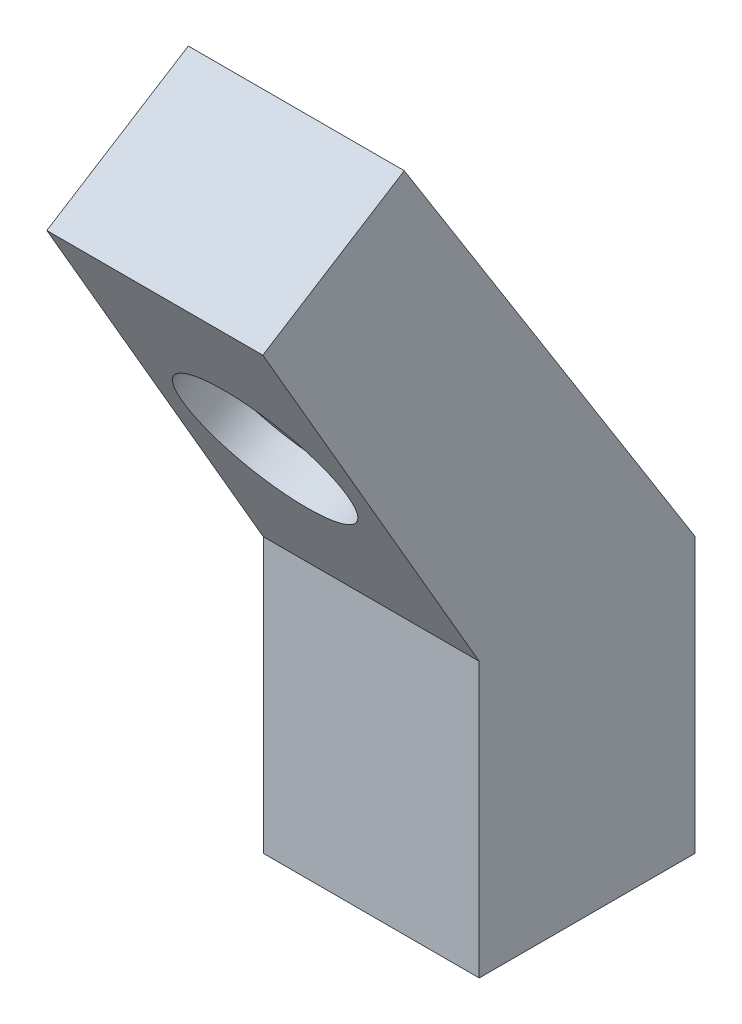
SolidWorks part; units mm, degrees
ref_plane "Front Plane" through (0, 0, 0) normal (0, 0, 1) x (1, 0, 0)
ref_plane "Top Plane" through (0, 0, 0) normal (0, 1, 0) x (1, 0, 0)
ref_plane "Right Plane" through (0, 0, 0) normal (1, 0, 0) x (0, 0, -1)
sketch "Sketch1" plane through (0, 0, 0) normal (0, 1, 0) x (1, 0, 0)
  line L1 (0, -58.2549) -> (0, 58.2549) construction
  line L5 (-58.2549, 0) -> (58.2549, 0) construction
  line L6 (0, 80) -> (-80, 80)
  line L7 (-80, 80) -> (-80, 0)
  line L8 (-80, 0) -> (-80, -80)
  line L9 (-80, -80) -> (0, -80)
  line L10 (80, 0) -> (80, -80)
  line L11 (80, -80) -> (0, -80)
  line L12 (80, 0) -> (80, 80)
  line L13 (80, 80) -> (0, 80)
  circle A0 centre (0, 0) radius 72.136
  point P16 (-80, 0)
  point P17 (0, 80)
  point P18 (80, 0)
  point P19 (0, -80)
extrude "Boss-Extrude1" add sketch "Sketch1" along normal blind 203.2 contours L8 L9 L11 L10 L12 L13 L6 L7
sketch "Sketch3" [suppressed] plane through (0, 330.2, 0) normal (0, 1, 0) x (1, 0, 0)
  circle A0 centre (0, 0) radius 61.468
  dimension "D1" = 122.936
sketch "Sketch4" plane through (80, 0, 0) normal (1, 0, 0) x (0, 0, -1)
  line L0 (80, 203.2) -> (-135.5261, 545.7261)
  line L1 (-135.5261, 545.7261) -> (-240.3374, 479.7762)
  line L2 (-240.3374, 479.7762) -> (-80, 203.2)
  line L3 (-80, 203.2) -> (80, 203.2)
  dimension "D1" = 319.6913
  dimension "D2" = 342.5261
extrude "Boss-Extrude2" add sketch "Sketch4" against normal blind 160.02 contours L2 L3 L0 L1
sketch "Sketch5" plane through (0, 16.4012, -28.2914) normal (0, -0.5015, 0.8651) x (1, 0, 0)
  line L0 (80, 535.6098) -> (80, 215.9186) construction
  line L1 (-80.02, 535.6098) -> (-80.02, 215.9186) construction
  circle A0 centre (0, 372.6182) radius 61.468
  point P0 (80, 375.7642)
  point P1 (-80.02, 375.7642)
  point P4 (0, 372.6182)
extrude "Cut-Extrude1" cut sketch "Sketch5" against normal blind 25.4
